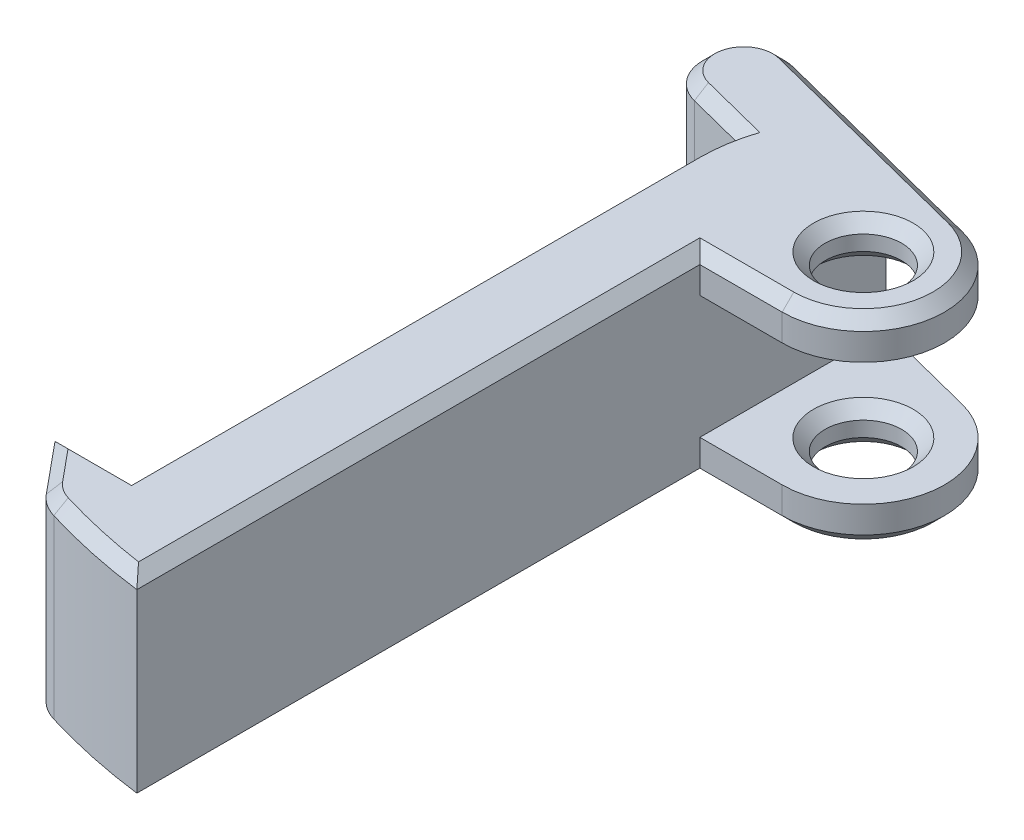
SolidWorks part; units mm, degrees
ref_plane "Front Plane" through (0, 0, 0) normal (0, 0, 1) x (1, 0, 0)
ref_plane "Top Plane" through (0, 0, 0) normal (0, 1, 0) x (1, 0, 0)
ref_plane "Right Plane" through (0, 0, 0) normal (1, 0, 0) x (0, 0, -1)
sketch "Sketch1" plane through (0, 0, 0) normal (0, 1, 0) x (1, 0, 0)
  line L1 (4.4163, 31.3911) -> (-5.3695, 33.8909)
  line L4 (-4, 28) -> (-4, 4)
  line L5 (-4, 4) -> (-7.3, 4)
  line L6 (-7.3, 4) -> (-4, 0)
  line L7 (-4, 0) -> (0, 0)
  line L8 (0, 0) -> (0, 24.5)
  line L9 (0, 24.5) -> (3.55, 24.5)
  line L10 (-4, 4) -> (-4, 0) construction
  line L11 (3.55, 28) -> (-4, 28) construction
  line L12 (3.55, 28) -> (-6.2358, 30.4998) construction
  line L13 (-6.2358, 30.4998) -> (-3.7651, 29.8687)
  line L15 (-6.2358, 30.4998) -> (-5.3695, 33.8909) construction
  line L16 (-7.4982, 32.6285) -> (-7.9313, 30.933) construction
  line L17 (-7.9313, 30.933) -> (-6.2358, 30.4998) construction
  line L18 (-5.8026, 33.9454) -> (3.55, 33.9454) construction
  line L19 (3.55, 33.9454) -> (3.55, 28) construction
  circle A0 centre (3.55, 28) radius 1.65
  arc A1 (3.55, 24.5) -> (4.4163, 31.3911) centre (3.55, 28) ccw
  arc A2 (-3.7651, 29.8687) -> (-4, 28) centre (3.55, 28) ccw
  arc A3 (-5.3695, 33.8909) -> (-6.2358, 30.4998) centre (-5.8026, 32.1954) ccw
  point P11 (-7.4982, 32.6285)
  dimension "D1" = 3.3
  dimension "D2" = 7
  dimension "D3" = 4
  dimension "D4" = 3.3
  dimension "D5" = 4
  dimension "D6" = 14.33
  dimension "D7" = 4.3
  dimension "D8" = 3.55
  dimension "D9" = 5.9454
  dimension "D10" = 28
  dimension "D11" = 7.55
  dimension "D12" = 3.5
  dimension "D14" = 104.33
  dimension "D15" = 10.1
extrude "Boss-Extrude1" add sketch "Sketch1" along normal blind 8.6
sketch "Sketch2" plane through (0, 0, -24.5) normal (0, 0, 1) x (1, 0, 0)
  line L0 (0, 8.6) -> (0, 0) construction
  line L1 (0, 1.65) -> (7.05, 1.65)
  line L2 (0, 1.65) -> (0, 6.95)
  line L3 (0, 6.95) -> (7.05, 6.95)
  line L4 (7.05, 1.65) -> (7.05, 6.95)
  line L5 (7.05, 0) -> (7.05, 8.6) construction
  line L6 (7.05, 6.95) -> (7.05, 8.6) construction
  line L7 (7.05, 1.65) -> (7.05, 0) construction
  dimension "D1" = 5.3
extrude "Cut-Extrude1" cut sketch "Sketch2" against normal through all
chamfer "Chamfer1" distance 0.5 angle 45 4 edges at (3.55, 0, -26.35) (3.55, 6.95, -26.35) (5.2, 1.65, -28) (3.55, 8.6, -26.35)
sketch "Sketch3" plane through (0, 0, 0) normal (0, 1, 0) x (1, 0, 0)
  line L4 (3.55, 28) -> (3.55, 0) construction
  line L5 (3.55, 0) -> (0, 0) construction
  line L6 (0, 0.226) -> (0, 0)
  line L7 (0, 0) -> (0, 24.5) construction
  line L8 (0, 0) -> (-4, 0)
  line L9 (-4, 0) -> (-5.1409, 1.3829)
  line L10 (-7.3, 4) -> (-4, 0) construction
  arc A1 (-5.1409, 1.3829) -> (0, 0.226) centre (3.55, 28) ccw
extrude "Cut-Extrude2" cut sketch "Sketch3" along normal through all
fillet "Fillet1" radius 2 1 edges at (-5.1409, 4.3, -1.3829)
chamfer "Chamfer2" distance 0.5 angle 45 24 edges at (-3.941, 0, -28.9417) (-5.65, 0, -4) (-4, 0, -16) (-5.0004, 0, -30.1842) (-7.4982, 0, -32.6285) (-0.4766, 0, -32.641) (-6.409, 0, -2.9201) (7.0227, 0, -27.5635) (-5.0836, 0, -1.448) (1.775, 0, -24.5) (0, 0, -12.363) (-2.2974, 0, -0.6174) (-3.941, 8.6, -28.9417) (-5.65, 8.6, -4) (-4, 8.6, -16) (-5.0004, 8.6, -30.1842) (-7.4982, 8.6, -32.6285) (-6.409, 8.6, -2.9201) (-0.4766, 8.6, -32.641) (-5.0836, 8.6, -1.448) (7.0227, 8.6, -27.5635) (-2.2974, 8.6, -0.6174) (0, 8.6, -12.363) (1.775, 8.6, -24.5)
